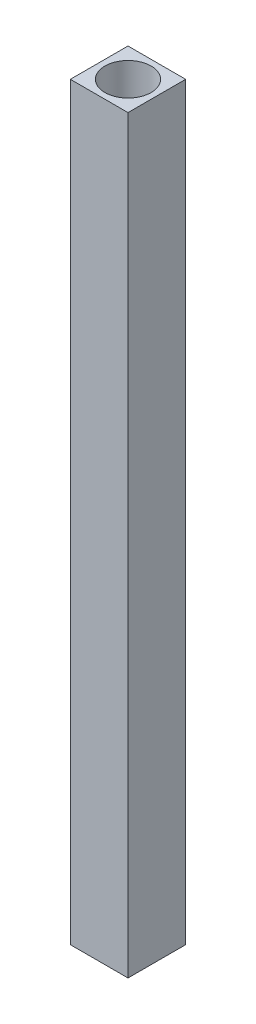
SolidWorks part; units mm, degrees
material "Thornel Mat VMA"
ref_plane "前视基准面" through (0, 0, 0) normal (0, 0, 1) x (1, 0, 0)
ref_plane "上视基准面" through (0, 0, 0) normal (0, 1, 0) x (1, 0, 0)
ref_plane "右视基准面" through (0, 0, 0) normal (1, 0, 0) x (0, 0, -1)
other "Configuration Table"
sketch "草图1" plane through (0, 0, 0) normal (0, 1, 0) x (1, 0, 0)
  line L1 (-5, -5) -> (5, -5)
  line L2 (-5, -5) -> (-5, 5)
  line L3 (-5, 5) -> (5, 5)
  line L4 (5, -5) -> (5, 5)
  line L5 (-5, -5) -> (5, 5) construction
  line L6 (-5, 5) -> (5, -5) construction
  point P0 (0, 0)
extrude "凸台-拉伸1" add sketch "草图1" along normal blind 130
ref_plane "基准面1" through (5, 130, 5) normal (0, -1, 0) x (-1, 0, 0)
sketch "草图2" plane through (5, 130, 5) normal (0, -1, 0) x (1, 0, 0)
  circle A0 centre (-5, -5) radius 4
extrude "切除-拉伸1" cut sketch "草图2" along normal blind 130
